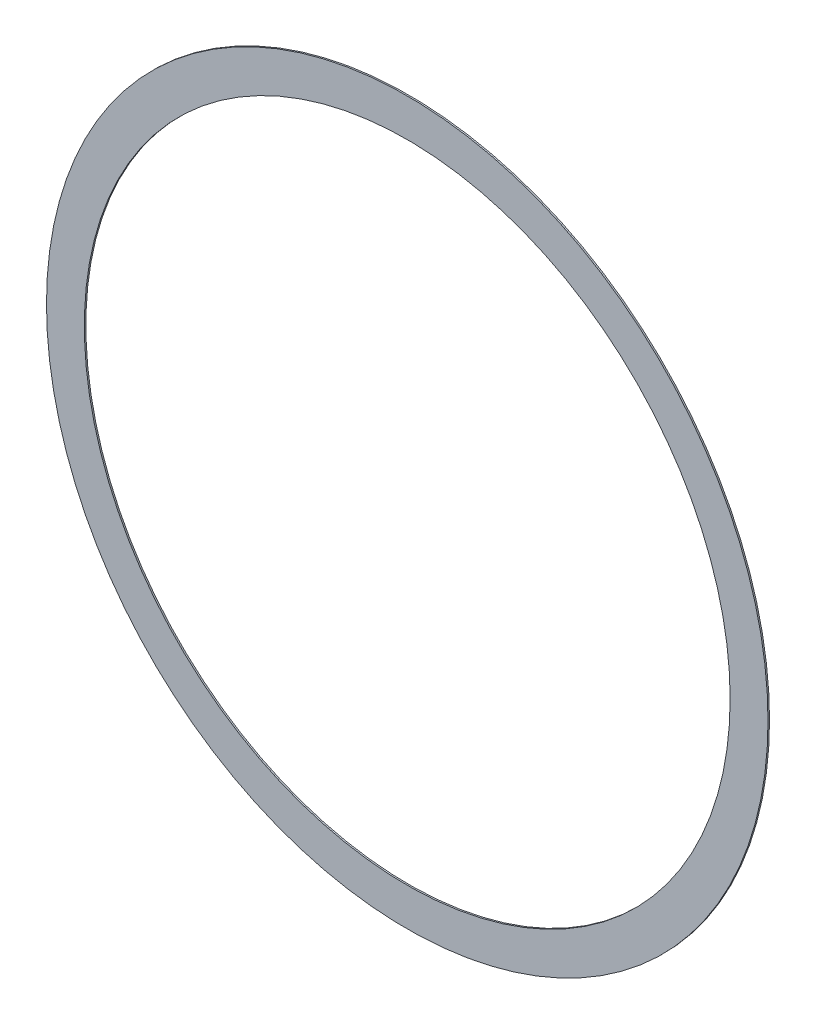
SolidWorks part; units mm, degrees
material "Galvanized Steel"
ref_plane "Front Plane" through (0, 0, 0) normal (0, 0, 1) x (1, 0, 0)
ref_plane "Top Plane" through (0, 0, 0) normal (0, 1, 0) x (1, 0, 0)
ref_plane "Right Plane" through (0, 0, 0) normal (1, 0, 0) x (0, 0, -1)
sketch "Sketch1" plane through (0, 0, 0) normal (0, 0, 1) x (1, 0, 0)
  circle A0 centre (0, 0) radius 426.5
  circle A1 centre (0, 0) radius 476.5
  dimension "D1" = 853
  dimension "D2" = 50
extrude "Boss-Extrude1" add sketch "Sketch1" along normal blind 2
